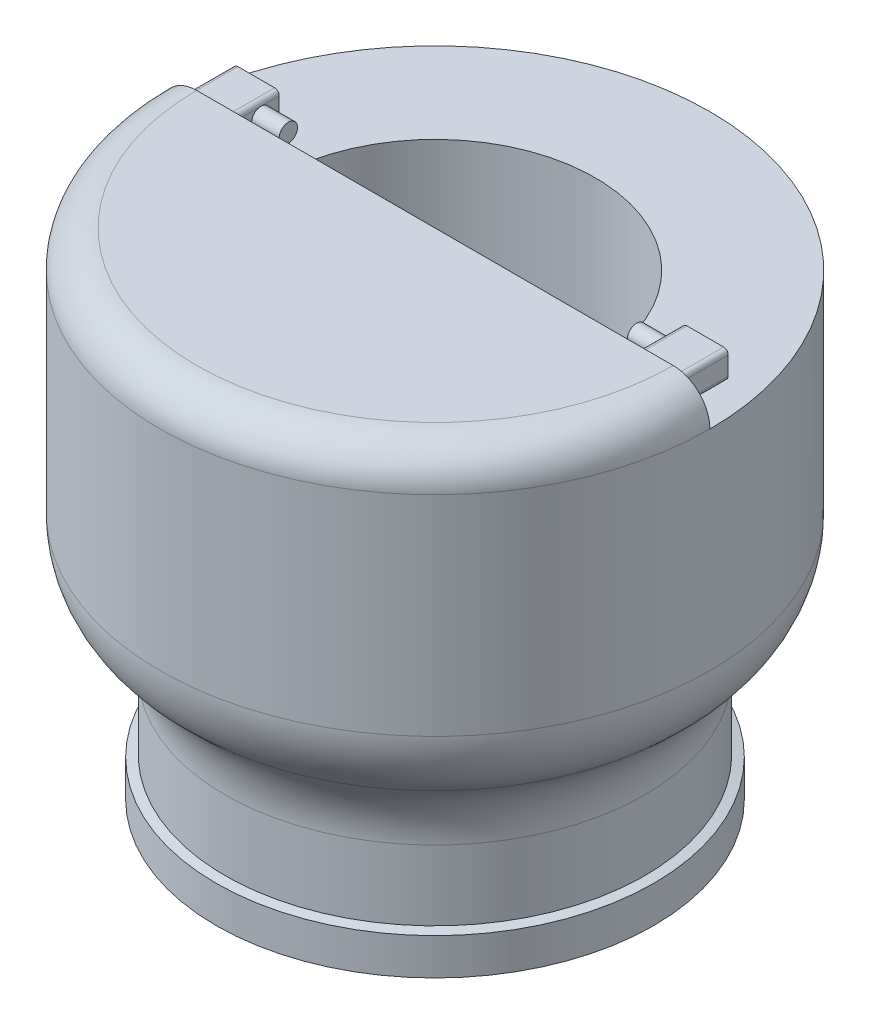
SolidWorks part; units mm, degrees
ref_plane "Front Plane" through (0, 0, 0) normal (0, 0, 1) x (1, 0, 0)
ref_plane "Top Plane" through (0, 0, 0) normal (0, 1, 0) x (1, 0, 0)
ref_plane "Right Plane" through (0, 0, 0) normal (1, 0, 0) x (0, 0, -1)
sketch "Sketch1" plane through (0, 0, 0) normal (0, 0, 1) x (1, 0, 0)
  line L0 (0, 0) -> (0, 57.8936) construction
  line L1 (20.9, 0) -> (23.8716, 0)
  line L2 (23.8716, 0) -> (23.8716, 4)
  line L3 (23.8716, 4) -> (22.9, 4.2367)
  line L4 (22.9, 4.2367) -> (22.9, 11.8746)
  line L6 (20.9, 0) -> (20.9, 14)
  line L12 (19.9, 15) -> (0, 15)
  line L17 (26.4721, 19.535) -> (26.4279, 19.4979)
  line L18 (30, 27.1583) -> (30, 50)
  line L20 (26, 54) -> (0, 54)
  line L22 (0, 15) -> (0, 54)
  arc A1 (30, 50) -> (26, 54) centre (26, 50) ccw
  arc A2 (26.4721, 19.535) -> (22.9, 11.8746) centre (32.9, 11.8746) ccw
  arc A3 (26.4279, 19.4979) -> (30, 27.1583) centre (20, 27.1583) ccw
  arc A6 (20.9, 14) -> (19.9, 15) centre (19.9, 14) ccw
  point P11 (22.9, 54)
  point P28 (28.5604, 23.4279)
  point P31 (20.9, 17)
  dimension "D9" = 4
  dimension "D4" = 30
  dimension "D16" = 10
  dimension "D19" = 1
  dimension "D2" = 4
  dimension "D3" = 1
  dimension "D6" = 2
  dimension "D7" = 2.9716
  dimension "D11" = 15
  dimension "D15" = 10
revolve "Revolve1" add sketch "Sketch1" angle 360 about L0
ref_plane "Plane1" through (0, 4, 0) normal (0, 1, 0) x (1, 0, 0)
sketch "Sketch3" plane through (0, 0, 0) normal (0, 0, 1) x (1, 0, 0)
  point P0 (1.2404, 19.1989)
ref_point "Point1"
ref_plane "Plane2" through (0, 0, 22.9) normal (0, 0, 1) x (1, 0, 0)
ref_plane "Plane3" through (0, 0, 30) normal (0, 0, 1) x (1, 0, 0)
ref_plane "Plane4" through (0, 50, 0) normal (0, -1, 0) x (-1, 0, 0)
sketch "Sketch9" plane through (0, 50, 0) normal (0, -1, 0) x (-1, 0, 0)
  line L0 (-30, 0) -> (30, 0)
  arc A0 (30, 0) -> (-30, 0) centre (0, 0) ccw
  circle A3 centre (0, 0) radius 26 construction
  dimension "D1" = 60
  dimension "D3" = 30
  dimension "D4" = 0
ref_plane "Plane5" through (0, 17, 0) normal (0, 1, 0) x (1, 0, 0)
sketch "Sketch11" plane through (0, 17, 0) normal (0, 1, 0) x (1, 0, 0)
  line L0 (-17.5, 0) -> (17.5, 0)
  arc A1 (-17.5, 0) -> (17.5, 0) centre (0, 0) cw
  dimension "D1" = 35
extrude "Cut-Extrude3" cut sketch "Sketch11" against normal blind 20 and the other way blind 45
ref_plane "Plane6" through (0, 0, -30) normal (0, 0, -1) x (-1, 0, 0)
extrude "Cut-Extrude5" cut sketch "Sketch9" against normal blind 5
sketch "Sketch13" plane through (0, 0, 0) normal (0, 0, -1) x (-1, 0, 0)
  line L1 (22.5, 53.5) -> (26.5, 53.5)
  line L2 (22, 53) -> (22, 51)
  line L3 (22.5, 50.5) -> (26.5, 50.5)
  line L4 (27, 53) -> (27, 51)
  line L5 (22, 53.5) -> (27, 50.5) construction
  line L6 (22, 50.5) -> (27, 53.5) construction
  line L9 (-26.5, 53.5) -> (-22.5, 53.5)
  line L10 (-27, 53) -> (-27, 51)
  line L11 (-26.5, 50.5) -> (-22.5, 50.5)
  line L12 (-22, 53) -> (-22, 51)
  line L13 (-27, 53.5) -> (-22, 50.5) construction
  line L14 (-27, 50.5) -> (-22, 53.5) construction
  arc A0 (26.5, 50.5) -> (27, 51) centre (26.5, 51) ccw
  arc A1 (27, 53) -> (26.5, 53.5) centre (26.5, 53) ccw
  arc A2 (22.5, 53.5) -> (22, 53) centre (22.5, 53) ccw
  arc A3 (22, 51) -> (22.5, 50.5) centre (22.5, 51) ccw
  arc A4 (-26.5, 53.5) -> (-27, 53) centre (-26.5, 53) ccw
  arc A5 (-27, 51) -> (-26.5, 50.5) centre (-26.5, 51) ccw
  arc A6 (-22.5, 50.5) -> (-22, 51) centre (-22.5, 51) ccw
  arc A7 (-22.5, 53.5) -> (-22, 53) centre (-22.5, 53) cw
  point P0 (24.5, 52)
  point P7 (-24.5, 52)
  dimension "D9" = 0.5
  dimension "D2" = 3
  dimension "D4" = 5
  dimension "D5" = 5
  dimension "D6" = 3
extrude "Boss-Extrude2" add sketch "Sketch13" along normal blind 5
sketch "Sketch14" plane through (22, 0, 0) normal (-1, 0, 0) x (0, 0, 1)
  line L0 (-5, 51) -> (0, 51) construction
  line L1 (-5, 51) -> (-5, 53) construction
  circle A0 centre (-3, 52) radius 1
  dimension "D1" = 2
  dimension "D2" = 1
  dimension "D3" = 2
extrude "Boss-Extrude3" add sketch "Sketch14" along normal blind 3
sketch "Sketch15" plane through (-22, 0, 0) normal (1, 0, 0) x (0, 0, -1)
  line L0 (5, 53) -> (0, 53) construction
  line L1 (5, 53) -> (5, 51) construction
  circle A0 centre (3, 52) radius 1
  dimension "D1" = 2
  dimension "D2" = 1
  dimension "D3" = 2
extrude "Boss-Extrude4" add sketch "Sketch15" along normal blind 3
sketch "Sketch16" plane through (0, 50, 0) normal (0, -1, 0) x (-1, 0, 0)
  line L0 (28.4704, -4) -> (-28.4704, -4)
  arc A0 (-28.4704, -4) -> (28.4704, -4) centre (0, 0) ccw
  arc A1 (-30, 0) -> (30, 0) centre (0, 0) ccw construction
  dimension "D1" = 1.25
  dimension "D2" = 4
  dimension "D3" = 4
extrude "Cut-Extrude6" cut sketch "Sketch16" along normal blind 22
